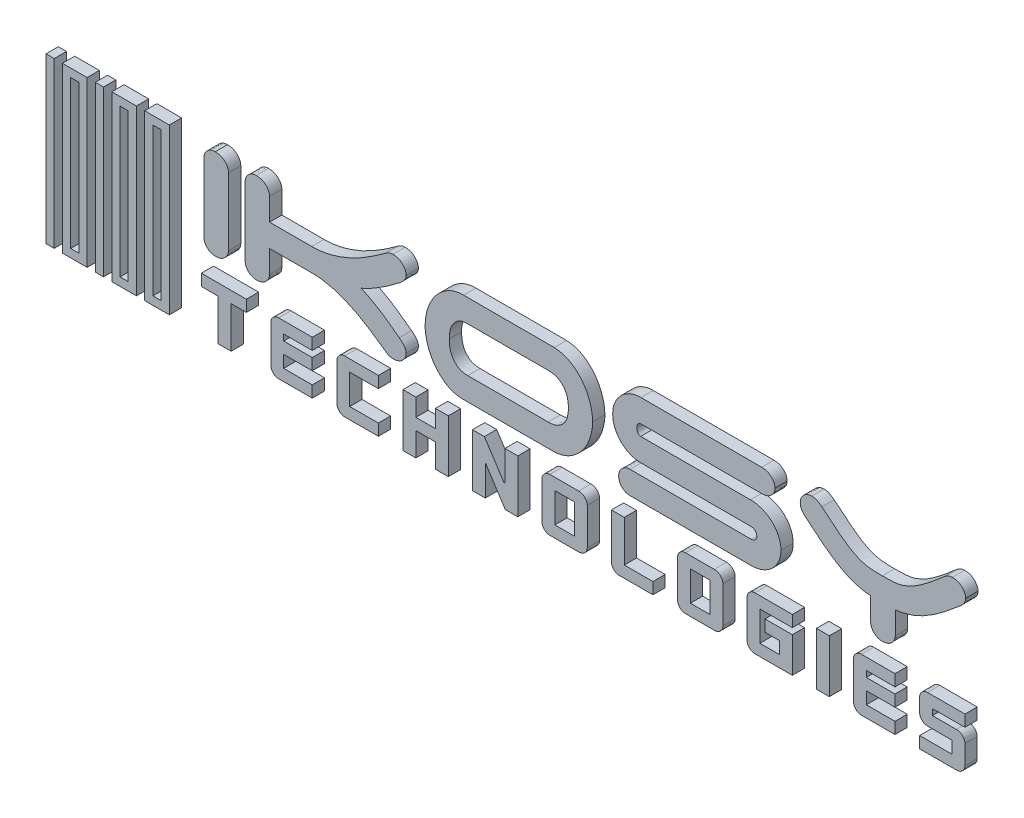
SolidWorks part; units mm, degrees
other "Text Extrude Y"
other "Text Extrude S"
other "Text Extrude O"
other "Text Extrude K"
other "Text Extrude I"
other "Symbol Extrude 3-1"
other "Symbol Extrude 2-0"
other "Symbol Extrude 1-1" parameters "D1"=6.2983, "D2"=2.0167, "D3"=11.6967, "D4"=11.6967, "D5"=1.4517, "D6"=1.4517, "D7"=14.1973, "D8"=14.1973, "D9"=30.15, "D10"=33.5, "D11"=33.5, "D12"=33.5, "D13"=30.15
ref_plane "Front Plane" through (0, 0, 0) normal (0, 0, 1) x (1, 0, 0)
ref_plane "Top Plane" through (0, 0, 0) normal (0, 1, 0) x (1, 0, 0)
ref_plane "Right Plane" through (0, 0, 0) normal (1, 0, 0) x (0, 0, -1)
sketch "Insertion Point Sketch" plane through (0, 0, 0) normal (0, 0, 1) x (1, 0, 0)
  line L0 (-3.25, -3.25) -> (-3.25, 0) construction
  line L1 (-3.25, -3.25) -> (0, -3.25) construction
  dimension "D1" = 3.25
  dimension "D2" = 3.25
sketch "Symbol Sketch" plane through (0, 0, 0) normal (0, 0, 1) x (1, 0, 0)
  line L1 (0, 33.5) -> (1.675, 33.5)
  line L2 (0, 33.5) -> (0, 0)
  line L3 (0, 0) -> (1.675, 0)
  line L4 (1.675, 33.5) -> (1.675, 0)
  line L5 (5.025, 31.825) -> (6.7, 31.825)
  line L6 (5.025, 31.825) -> (5.025, 1.675)
  line L7 (5.025, 1.675) -> (6.7, 1.675)
  line L8 (6.7, 31.825) -> (6.7, 1.675)
  line L9 (3.35, 33.5) -> (8.375, 33.5)
  line L10 (3.35, 33.5) -> (3.35, 0)
  line L11 (3.35, 0) -> (8.375, 0)
  line L12 (8.375, 33.5) -> (8.375, 0)
  line L13 (10.05, 33.5) -> (11.725, 33.5)
  line L14 (10.05, 33.5) -> (10.05, 0)
  line L15 (10.05, 0) -> (11.725, 0)
  line L16 (11.725, 33.5) -> (11.725, 0)
  line L17 (13.4, 33.5) -> (18.425, 33.5)
  line L18 (13.4, 33.5) -> (13.4, 0)
  line L19 (13.4, 0) -> (18.425, 0)
  line L20 (18.425, 33.5) -> (18.425, 0)
  line L21 (15.075, 31.825) -> (16.75, 31.825)
  line L22 (15.075, 31.825) -> (15.075, 1.675)
  line L23 (15.075, 1.675) -> (16.75, 1.675)
  line L24 (16.75, 31.825) -> (16.75, 1.675)
  line L25 (20.1, 33.5) -> (25.125, 33.5)
  line L26 (20.1, 33.5) -> (20.1, 0)
  line L27 (20.1, 0) -> (25.125, 0)
  line L28 (25.125, 33.5) -> (25.125, 0)
  line L29 (21.775, 31.825) -> (23.45, 31.825)
  line L30 (21.775, 31.825) -> (21.775, 1.675)
  line L31 (21.775, 1.675) -> (23.45, 1.675)
  line L32 (23.45, 31.825) -> (23.45, 1.675)
  dimension "D1" = 1.675
  dimension "D2" = 1.675
  dimension "D3" = 1.675
  dimension "D4" = 1.675
  dimension "D5" = 1.675
  dimension "D6" = 1.675
  dimension "D7" = 1.675
  dimension "D8" = 33.5
  dimension "D9" = 1.675
  dimension "D10" = 1.675
  dimension "D11" = 1.675
  dimension "D12" = 1.675
  dimension "D13" = 1.675
extrude "Symbol Extrude" add sketch "Symbol Sketch" along normal blind 2.5
sketch "Text Sketch" plane through (0, 0, 0) normal (0, 0, 1) x (1, 0, 0)
  line L0 (25.125, 33.5) -> (187.5, 33.5) construction
  line L1 (187.5, 33.5) -> (187.5, 0) construction
  text T0 "ikosy" font "Space Age" height 18.425
  text T1 "TECHNOLOGIES" font "Alien Encounters Solid" height 10.75
  dimension "D1" = 30.125
  dimension "D2" = 12.075
  dimension "D3" = 1.1
  dimension "D4" = 187.5
extrude "Text Extrude" add sketch "Text Sketch" along normal blind 2.5 separate body
equation "\"Logo Height\"= \"Total Height\" - 2 * \"Border\""
equation "\"Total Height\"= 40mm"
equation "\"Border\"= 3.25mm"
equation "\"Symbol Width\"= \"Logo Height\" * 0.75"
equation "\"Line Width\"= \"Symbol Width\" / 15"
equation "\"D2@Symbol Sketch\" = \"Line Width\""
equation "\"D1@Symbol Sketch\" = \"Line Width\""
equation "\"D3@Symbol Sketch\" = \"Line Width\""
equation "\"D4@Symbol Sketch\" = \"Line Width\""
equation "\"D5@Symbol Sketch\" = \"Line Width\""
equation "\"D6@Symbol Sketch\" = \"Line Width\""
equation "\"D7@Symbol Sketch\" = \"Line Width\""
equation "\"D8@Symbol Sketch\" = \"Logo Height\""
equation "\"D9@Symbol Sketch\" = \"Line Width\""
equation "\"D10@Symbol Sketch\" = \"Line Width\""
equation "\"D11@Symbol Sketch\" = \"Line Width\""
equation "\"D12@Symbol Sketch\" = \"Line Width\""
equation "\"D13@Symbol Sketch\" = \"Line Width\""
equation "\"Ikosy X Position\"= \"Symbol Width\" + 5mm"
equation "\"Ikosy Y Position\"= ( 1 - 0.55 ) * \"Logo Height\" - 3"
equation "\"D2@Text Sketch\" = \"Ikosy Y Position\""
equation "\"D1@Text Sketch\" = \"Ikosy X Position\""
equation "\"D1@Insertion Point Sketch\" = \"Border\""
equation "\"D2@Insertion Point Sketch\" = \"Border\""
